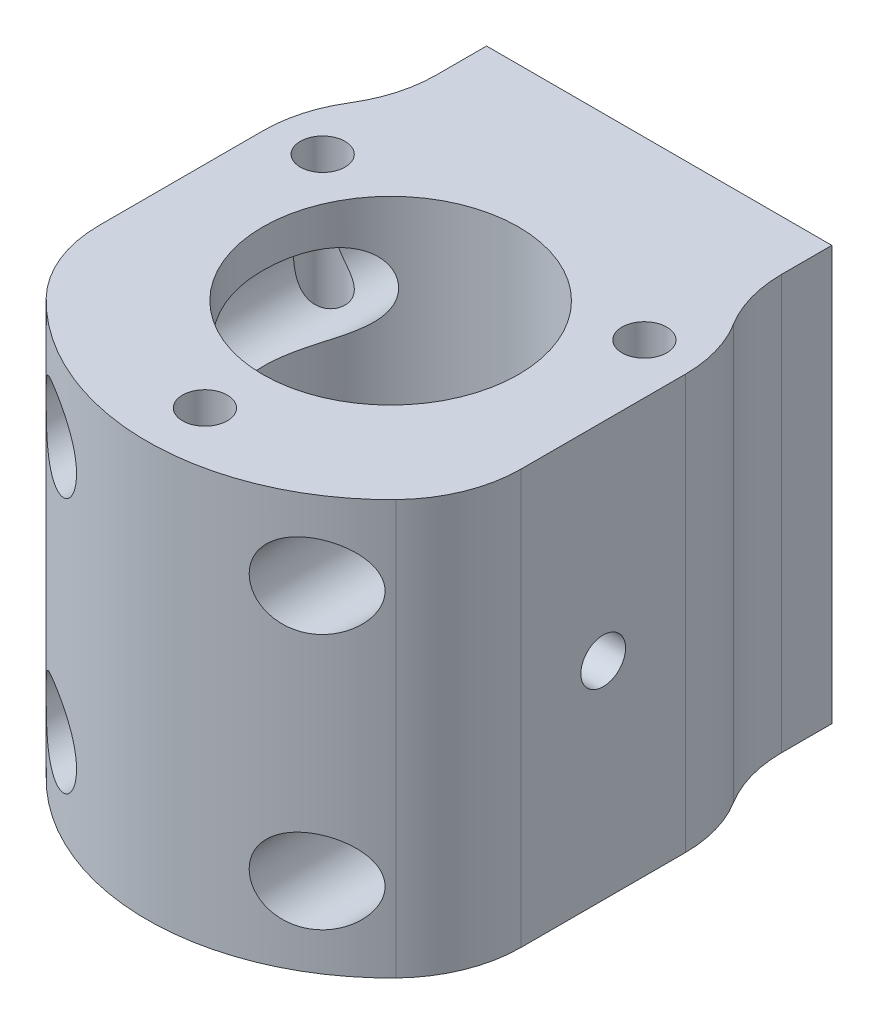
SolidWorks part; units mm, degrees
ref_plane "Plan de face" through (0, 0, 0) normal (0, 0, 1) x (1, 0, 0)
ref_plane "Plan de dessus" through (0, 0, 0) normal (0, 1, 0) x (1, 0, 0)
ref_plane "Plan de droite" through (0, 0, 0) normal (1, 0, 0) x (0, 0, -1)
sketch "Esquisse1" plane through (0, 0, 0) normal (0, 0, 1) x (1, 0, 0)
  line L0 (-13.5, 16.2) -> (13.5, -16.2) construction
  line L1 (-13.5, 16.2) -> (13.5, 16.2)
  line L2 (-13.5, 16.2) -> (-13.5, -16.2)
  line L3 (-13.5, -16.2) -> (13.5, -16.2)
  line L4 (13.5, 16.2) -> (13.5, -16.2)
  dimension "D1" = 32.4
  dimension "D2" = 27
extrude "Boss.-Extru.1" add sketch "Esquisse1" along normal blind 3
sketch "Esquisse3" plane through (0, -16.2, 0) normal (0, -1, 0) x (1, 0, 0)
  line L0 (-13.5, 3) -> (13.5, 3) construction
  line L1 (-13.5, 3) -> (-13.5, 7.5593)
  line L2 (0, 21) -> (0, 3) construction
  line L3 (13.5, 7.5593) -> (13.5, 3)
  line L4 (13.5, 3) -> (13.5, 0)
  line L5 (13.5, 0) -> (-13.5, 0)
  line L6 (-13.5, 0) -> (-13.5, 3)
  arc A0 (13.5, 7.5593) -> (-13.5, 7.5593) centre (0, 21) ccw
  circle A1 centre (0, 21) radius 10
  dimension "D1" = 38.1
  dimension "D3" = 20
  dimension "D2" = 18
extrude "Boss.-Extru.2" add sketch "Esquisse3" against normal up to surface (32.4 mm away) up to face at (0, 16.2, 1.5)
fillet "Congé1" radius 10 2 edges at (13.5, 0, 7.5593) (-13.5, 0, 7.5593)
sketch "Esquisse2" plane through (0, 0, 0) normal (0, 0, 1) x (1, 0, 0)
  line L0 (-10, 10) -> (10, -10) construction
  line L1 (-10, 10) -> (10, 10) construction
  line L2 (-10, 10) -> (-10, -10) construction
  line L3 (-10, -10) -> (10, -10) construction
  line L4 (10, 10) -> (10, -10) construction
  circle A0 centre (-10, 10) radius 1.5
  circle A1 centre (10, 10) radius 1.5
  circle A2 centre (10, -10) radius 1.5
  circle A3 centre (-10, -10) radius 1.5
  dimension "D2" = 3
  dimension "D1" = 20
  dimension "D3" = 20
extrude "Enlèv. mat.-Extru.1" cut sketch "Esquisse2" along normal up to next
sketch "Esquisse4" plane through (0, 16.2, 0) normal (0, 1, 0) x (1, 0, 0)
  line L0 (0, -31) -> (0, -33.775) construction
  line L1 (0, -33.775) -> (0, -37.275) construction
  line L2 (0, -37.275) -> (0, -40.05) construction
  circle A0 centre (0, -35.525) radius 1.75
  circle A1 centre (0, -21) radius 10 construction
  arc A2 (-15.4105, -9.8009) -> (15.4105, -9.8009) centre (0, -21) ccw construction
  point P6 (0, -35.0693)
  dimension "D1" = 3.5
extrude "Enlèv. mat.-Extru.2" cut sketch "Esquisse4" against normal up to next
pattern_circular "Répétition circulaire1" count 3 every 120 about axis through (0, 0, 21) along (0, 1, 0) of "Enlèv. mat.-Extru.2"
ref_plane "Plan1" through (0, 0, 3) normal (0, 0, -1) x (-1, 0, 0)
sketch "Esquisse5" plane through (0, 0, 3) normal (0, 0, -1) x (-1, 0, 0)
  circle A0 centre (-10, 10) radius 3.25
  circle A1 centre (10, 10) radius 3.25
  circle A2 centre (-10, -10) radius 3.25
  circle A3 centre (10, -10) radius 3.25
  dimension "D1" = 6.5
extrude "Enlèv. mat.-Extru.3" cut sketch "Esquisse5" against normal up to next
sketch "Esquisse7" plane through (0, 16.2, 0) normal (0, 1, 0) x (1, 0, 0)
  line L0 (-16.5, -11.4788) -> (-16.5, -30.5212)
  line L1 (16.5, -30.5212) -> (16.5, -11.4788)
  line L2 (-16.5, -21) -> (16.5, -21) construction
  arc A0 (-16.5, -11.4788) -> (-16.5, -30.5212) centre (0, -21) ccw
  arc A1 (-15.4105, -9.8009) -> (15.4105, -9.8009) centre (0, -21) ccw construction
  arc A2 (16.5, -11.4788) -> (16.5, -30.5212) centre (0, -21) cw
  dimension "D1" = 33
extrude "Enlèv. mat.-Extru.5" cut sketch "Esquisse7" against normal up to next
fillet "Congé2" radius 10 4 edges at (16.5, 0, 11.4788) (16.5, 0, 30.5212) (-16.5, 0, 30.5212) (-16.5, 0, 11.4788)
sketch "Esquisse8" plane through (-16.5, 0, 0) normal (-1, 0, 0) x (0, 0, 1)
  line L0 (20.8774, 16.2) -> (20.8774, -16.2) construction
  line L1 (27.297, 16.2) -> (14.4578, 16.2) construction
  line L2 (14.4578, -16.2) -> (27.297, -16.2) construction
  circle A0 centre (20.8774, 0) radius 1.75
  dimension "D1" = 3.5
extrude "Enlèv. mat.-Extru.6" cut sketch "Esquisse8" against normal up to surface (33 mm away) up to face at (16.5, 0, 20.8774)
ref_plane "Plan2" through (-13.5, 0, 0) normal (-1, 0, 0) x (0, 0, 1)
sketch "Esquisse9" plane through (-13.5, 0, 0) normal (-1, 0, 0) x (0, 0, 1)
  line L1 (24.3415, 0) -> (22.6095, 3)
  line L2 (22.6095, 3) -> (19.1454, 3)
  line L3 (19.1454, 3) -> (17.4133, 0)
  line L4 (17.4133, 0) -> (19.1454, -3)
  line L5 (19.1454, -3) -> (22.6095, -3)
  line L6 (22.6095, -3) -> (24.3415, 0)
  circle A0 centre (20.8774, 0) radius 3 construction
  point P1 (0, 0)
  dimension "D1" = 6
extrude "Enlèv. mat.-Extru.7" cut sketch "Esquisse9" against normal up to next
mirror "Symétrie1" about plane through (0, 0, 0) normal (1, 0, 0) of "Enlèv. mat.-Extru.7"
